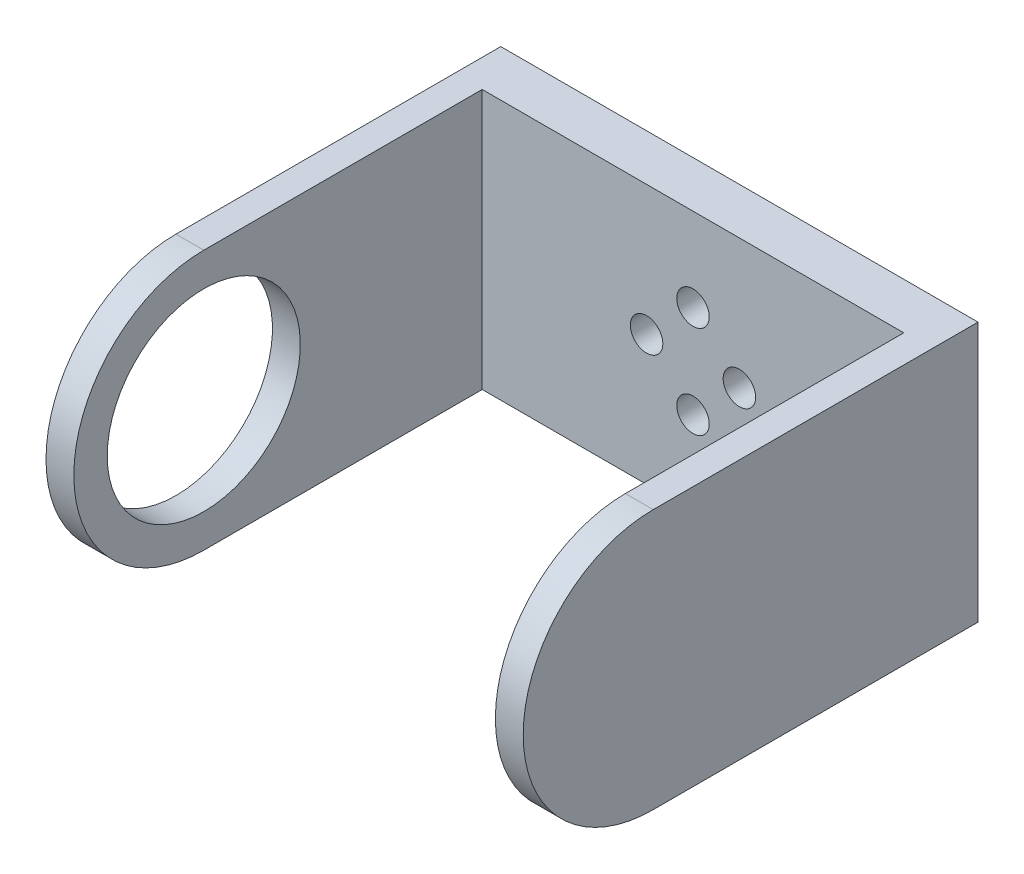
SolidWorks part; units mm, degrees
material "ABS"
ref_plane "Front Plane" through (0, 0, 0) normal (0, 0, 1) x (1, 0, 0)
ref_plane "Top Plane" through (0, 0, 0) normal (0, 1, 0) x (1, 0, 0)
ref_plane "Right Plane" through (0, 0, 0) normal (1, 0, 0) x (0, 0, -1)
sketch "Sketch1" plane through (0, 0, 0) normal (0, 0, 1) x (1, 0, 0)
  line L1 (-25.71, 14) -> (25.71, 14)
  line L2 (-25.71, 14) -> (-25.71, -14)
  line L3 (-25.71, -14) -> (25.71, -14)
  line L4 (25.71, 14) -> (25.71, -14)
  line L5 (-25.71, 14) -> (25.71, -14) construction
  line L6 (-25.71, -14) -> (25.71, 14) construction
  point P0 (0, 0)
  dimension "D1" = 51.42
  dimension "D2" = 28
extrude "Boss-Extrude1" add sketch "Sketch1" along normal blind 5
sketch "Sketch3" plane through (0, 0, 5) normal (0, 0, 1) x (1, 0, 0)
  line L0 (-25.71, 14) -> (-25.71, -14)
  line L1 (-25.71, -14) -> (-22.71, -14)
  line L2 (-25.71, -14) -> (25.71, -14) construction
  line L3 (-22.71, -14) -> (-22.71, 14)
  line L4 (25.71, 14) -> (-25.71, 14) construction
  line L5 (-22.71, 14) -> (-25.71, 14)
  line L6 (25.71, -14) -> (22.71, -14)
  line L7 (22.71, -14) -> (22.71, 14)
  line L8 (22.71, 14) -> (25.71, 14)
  line L9 (25.71, 14) -> (25.71, -14)
  dimension "D1" = 3
  dimension "D2" = 3
extrude "Boss-Extrude2" add sketch "Sketch3" along normal blind 30
sketch "Sketch5" plane through (-25.71, 0, 0) normal (-1, 0, 0) x (0, 0, 1)
  line L4 (0, 14) -> (0, -14)
  line L5 (0, -14) -> (35, -14)
  line L6 (35, -14) -> (35, 14)
  line L7 (35, 14) -> (0, 14)
  line L10 (35, -14) -> (35, 14)
  arc A0 (35, 14) -> (35, -14) centre (35, 0) cw
  dimension "D1" = 0
  dimension "D2" = 14
extrude "Boss-Extrude4" add sketch "Sketch5" against normal blind 3
sketch "Sketch6" plane through (-25.71, 0, 0) normal (-1, 0, 0) x (0, 0, 1)
  circle A0 centre (35, 0) radius 10.4
  dimension "D1" = 20.8
extrude "Cut-Extrude1" cut sketch "Sketch6" against normal blind 4
sketch "Sketch7" plane through (25.71, 0, 0) normal (1, 0, 0) x (0, 0, -1)
  line L4 (0, -14) -> (0, 14)
  line L5 (0, 14) -> (-35, 14)
  line L6 (-35, 14) -> (-35, -14)
  line L7 (-35, -14) -> (0, -14)
  line L10 (-35, 14) -> (-35, -14)
  arc A0 (-35, 14) -> (-35, -14) centre (-35, 0) ccw
  dimension "D1" = 14
  dimension "D2" = 0
extrude "Boss-Extrude5" add sketch "Sketch7" against normal blind 3
sketch "Sketch8" plane through (0, 0, 0) normal (0, 0, -1) x (-1, 0, 0)
  line L0 (-25.71, 14) -> (25.71, 14) construction
  line L1 (25.71, 14) -> (25.71, -14) construction
  line L2 (-2.5626, 0) -> (2.6505, 0) construction
  circle A1 centre (0, 5) radius 1.75
  circle A2 centre (-5, 0) radius 1.75
  circle A3 centre (5, 0) radius 1.75
  circle A4 centre (0, -5) radius 1.75
  dimension "D1" = 3.5
  dimension "D3" = 5
  dimension "D2" = 3.5
  dimension "D4" = 14
  dimension "D5" = 5
  dimension "D6" = 25.71
  dimension "D7" = 3.5
extrude "Cut-Extrude2" cut sketch "Sketch8" against normal blind 10
